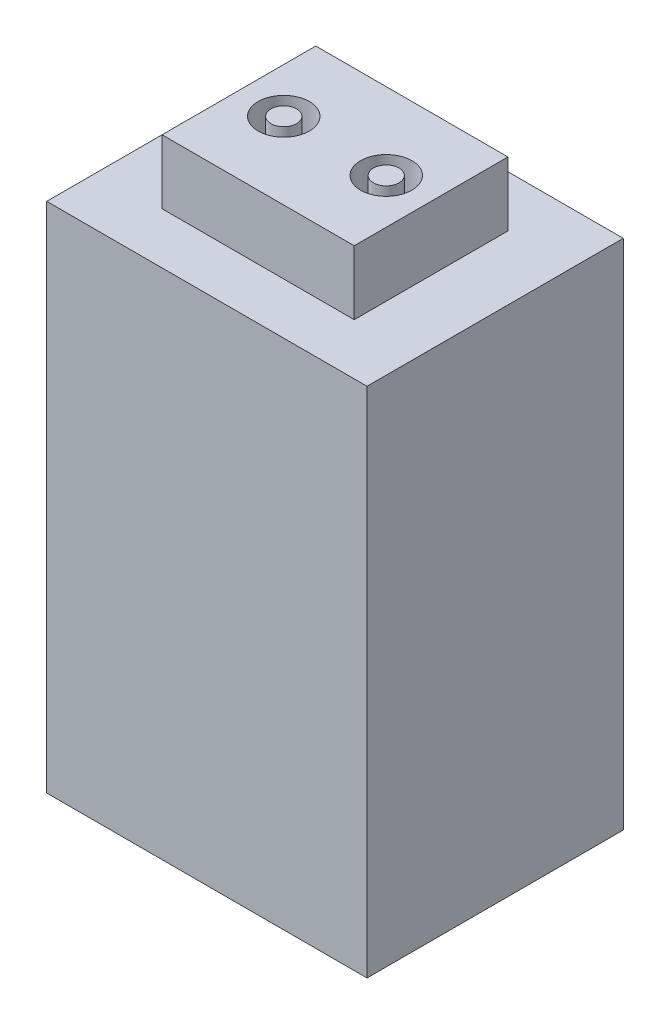
SolidWorks part; units mm, degrees
ref_plane "Front Plane" through (0, 0, 0) normal (1, 0, 0) x (0, 1, 0)
ref_plane "Top Plane" through (0, 0, 0) normal (0, 0, 1) x (0, 1, 0)
ref_plane "Right Plane" through (0, 0, 0) normal (0, 1, 0) x (-1, 0, 0)
sketch "Sketch1" plane through (0, 0, 0) normal (0, 0, 1) x (0, 1, 0)
  line L1 (0, 0) -> (80, 0)
  line L2 (0, 0) -> (0, 50)
  line L3 (0, 50) -> (80, 50)
  line L4 (80, 0) -> (80, 50)
  dimension "D1" = 80
  dimension "D2" = 50
extrude "Boss-Extrude1" add sketch "Sketch1" along normal blind 40
sketch "Sketch2" plane through (0, 80, 0) normal (0, 1, 0) x (-1, 0, 0)
  line L0 (0, 0) -> (50, 40) construction
  line L2 (40, 8) -> (10, 8)
  line L3 (40, 8) -> (40, 32)
  line L4 (40, 32) -> (10, 32)
  line L5 (10, 8) -> (10, 32)
  line L6 (40, 8) -> (10, 32) construction
  line L7 (40, 32) -> (10, 8) construction
  point P4 (25, 20)
  point P9 (8.426, 33.2592)
  dimension "D1" = 30
extrude "Boss-Extrude2" add sketch "Sketch2" along normal blind 10
sketch "Sketch3" plane through (0, 90, 0) normal (0, 1, 0) x (-1, 0, 0)
  line L0 (10, 20) -> (40, 20) construction
  line L1 (10, 32) -> (10, 8) construction
  line L2 (40, 8) -> (40, 32) construction
  line L3 (25, 32) -> (25, 8) construction
  line L4 (40, 32) -> (10, 32) construction
  line L5 (10, 8) -> (40, 8) construction
  circle A0 centre (17, 20) radius 4
  circle A1 centre (33, 20) radius 4
  circle A2 centre (17, 20) radius 2
  circle A3 centre (33, 20) radius 2
  dimension "D1" = 8
  dimension "D2" = 8
  dimension "D5" = 4
  dimension "D6" = 4
  dimension "D3" = 8
  dimension "D4" = 8
extrude "Cut-Extrude1" cut sketch "Sketch3" against normal blind 5
